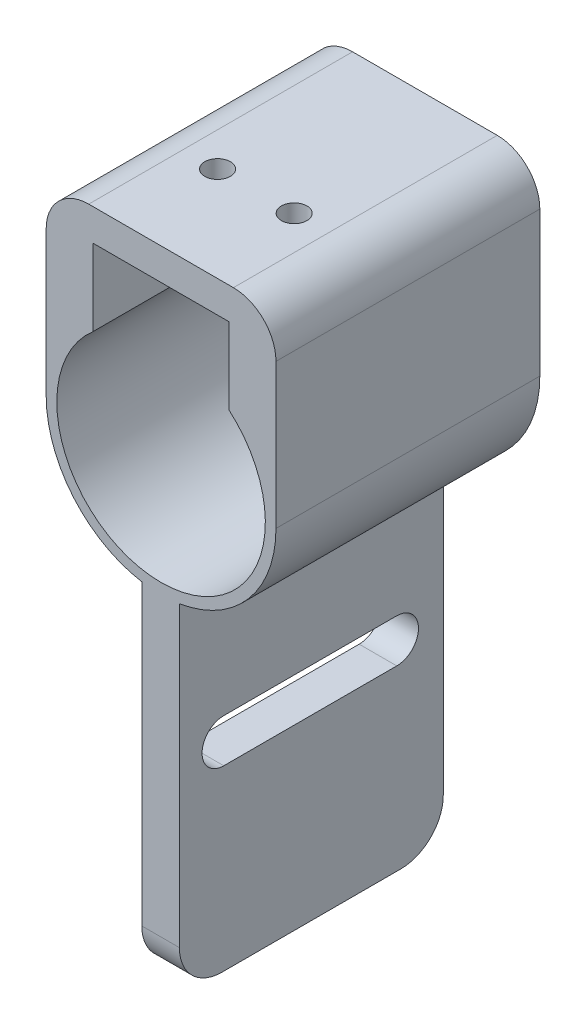
SolidWorks part; units mm, degrees
ref_plane "Front Plane" through (0, 0, 0) normal (0, 0, 1) x (1, 0, 0)
ref_plane "Top Plane" through (0, 0, 0) normal (0, 1, 0) x (1, 0, 0)
ref_plane "Right Plane" through (0, 0, 0) normal (1, 0, 0) x (0, 0, -1)
sketch "Sketch1" plane through (0, 0, 0) normal (0, 0, 1) x (1, 0, 0)
  line L0 (0, -55) -> (0, 55) construction
  line L2 (-13.5, 0) -> (-13.5, 22)
  line L3 (-13.5, 22) -> (13.5, 22)
  line L4 (13.5, 0) -> (13.5, 22)
  line L5 (-2.2647, -53.3268) -> (2.1554, -53.3268)
  line L6 (-2.2647, -53.3268) -> (-2.2647, -13.3087)
  line L8 (2.1554, -53.3268) -> (2.1554, -13.3268)
  line L9 (-2.2647, -53.3268) -> (2.0442, -13.3443) construction
  line L10 (-1.9441, -13.3593) -> (2.1554, -53.3268) construction
  arc A0 (-13.5, 0) -> (-2.2647, -13.3087) centre (0, 0) ccw
  circle A1 centre (0, 0) radius 12.25
  arc A2 (2.1554, -13.3268) -> (13.5, 0) centre (0, 0) ccw
  point P7 (0, -32.3128)
  dimension "D1" = 27
  dimension "D2" = 24.5
  dimension "D3" = 40
  dimension "D4" = 22
extrude "Boss-Extrude2" add sketch "Sketch1" along normal blind 31
sketch "Sketch2" plane through (0, 0, 31) normal (0, 0, 1) x (1, 0, 0)
  line L0 (-8, 9.277) -> (8, 9.277)
  line L1 (8, 9.277) -> (8, 18.277)
  line L2 (-8, 9.277) -> (-8, 18.277)
  line L3 (-8, 18.277) -> (8, 18.277)
  circle A0 centre (0, 0) radius 12.25 construction
  dimension "D1" = 9
  dimension "D2" = 16
extrude "Cut-Extrude1" cut sketch "Sketch2" against normal blind 15
sketch "Sketch3" plane through (0, 18.277, 0) normal (0, -1, 0) x (1, 0, 0)
  line L0 (0, -17.05) -> (0, 17.05) construction
  line L1 (-8, 16) -> (-4.5, 16) construction
  line L2 (-8, 16) -> (-8, 19.86) construction
  line L3 (-8, 19.86) -> (-4.5, 19.86) construction
  line L4 (-4.5, 16) -> (-4.5, 19.86) construction
  line L5 (8, 19.86) -> (4.5, 19.86) construction
  line L6 (4.5, 16) -> (4.5, 19.86) construction
  line L7 (8, 16) -> (4.5, 16) construction
  line L8 (8, 16) -> (8, 19.86) construction
  circle A0 centre (-4.5, 19.86) radius 1.5
  circle A1 centre (4.5, 19.86) radius 1.5
  dimension "D3" = 3
  dimension "D4" = 3
  dimension "D1" = 9
extrude "Cut-Extrude2" cut sketch "Sketch3" against normal blind 15
sketch "Sketch4" plane through (2.1554, 0, 0) normal (1, 0, 0) x (0, 0, -1)
  line L0 (-25.7873, -29.8768) -> (-5.4626, -29.8768) construction
  line L1 (-25.7873, -27.3268) -> (-5.4626, -27.3268)
  line L2 (-25.7873, -32.4268) -> (-5.4626, -32.4268)
  line L3 (-31, -13.3268) -> (0, -13.3268) construction
  arc A0 (-25.7873, -27.3268) -> (-25.7873, -32.4268) centre (-25.7873, -29.8768) ccw
  arc A1 (-5.4626, -32.4268) -> (-5.4626, -27.3268) centre (-5.4626, -29.8768) ccw
  point P2 (-15.625, -29.8768)
  dimension "D1" = 2.55
  dimension "D2" = 14
extrude "Cut-Extrude3" cut sketch "Sketch4" against normal blind 15
fillet "Fillet1" radius 5 4 edges at (-0.0546, -53.3268, 0) (-0.0546, -53.3268, 31) (-13.5, 22, 15.5) (13.5, 22, 15.5)
